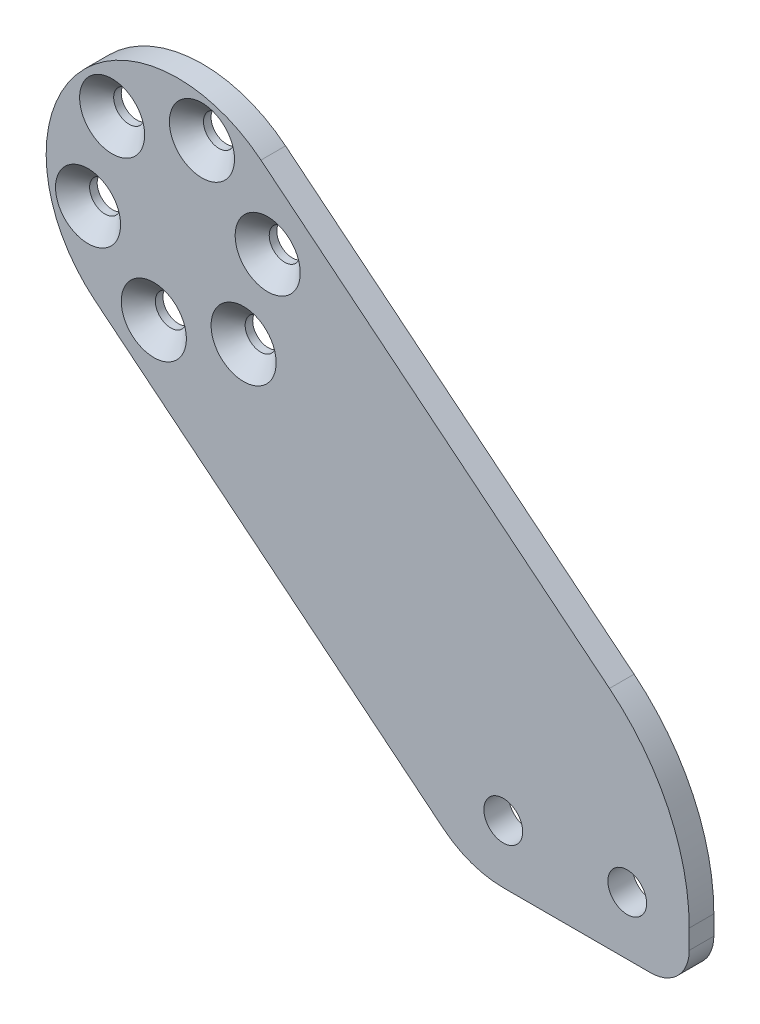
SolidWorks part; units mm, degrees
ref_plane "Front Plane" through (0, 0, 0) normal (0, 0, 1) x (1, 0, 0)
ref_plane "Top Plane" through (0, 0, 0) normal (0, 1, 0) x (1, 0, 0)
ref_plane "Right Plane" through (0, 0, 0) normal (1, 0, 0) x (0, 0, -1)
sketch "Sketch1" plane through (0, 0, 0) normal (0, 0, 1) x (1, 0, 0)
  line L0 (34.2613, -49.7518) -> (-10.7219, -13.1924)
  line L5 (-8.4853, 8.4853) -> (0, 0) construction
  line L6 (0, -12) -> (0, 12) construction
  line L8 (55.7052, -23.367) -> (10.7219, 13.1924)
  line L9 (42, -45) -> (58, -45) construction
  line L10 (42, -45) -> (42, -52.5) construction
  line L14 (66, -45) -> (66, -52.5)
  line L16 (42, -52.5) -> (66, -52.5)
  line L17 (34, -37.5) -> (34, -52.5) construction
  line L18 (34, -52.5) -> (42, -52.5) construction
  line L19 (66, -37.5) -> (66, -45) construction
  line L20 (66, -37.5) -> (34, -37.5) construction
  line L21 (66, -45) -> (58, -45) construction
  line L22 (34.2613, -49.7518) -> (55.7052, -23.367) construction
  line L23 (50, -37.5) -> (50, -52.5) construction
  arc A0 (10.7219, 13.1924) -> (-10.7219, -13.1924) centre (0, 0) ccw
  circle A3 centre (-8.4853, 8.4853) radius 2
  circle A5 centre (3.1058, 11.5911) radius 2
  circle A6 centre (11.5911, 3.1058) radius 2
  circle A7 centre (8.4853, -8.4853) radius 2
  circle A10 centre (0, 0) radius 12 construction
  circle A11 centre (42, -45) radius 2.5
  circle A12 centre (58, -45) radius 2.5
  circle A14 centre (-3.1058, -11.5911) radius 2
  circle A15 centre (-11.5911, -3.1058) radius 2
  circle A16 centre (0, 0) radius 50 construction
  arc A17 (34.2613, -49.7518) -> (42, -52.5) centre (42, -40.2301) ccw
  arc A18 (55.7052, -23.367) -> (66, -45) centre (38.1233, -45) cw
  point P4 (50, -45)
  point P30 (0, 0)
  point P35 (0, 0)
  dimension "D2" = 34
  dimension "D4" = 4
  dimension "D5" = 50
  dimension "D8" = 32
  dimension "D7" = 5
  dimension "D3" = 24
  dimension "D12" = 100
  dimension "D1" = 45
  dimension "D10" = 16
  dimension "D13" = 45
  dimension "D15" = 15
  dimension "D6" = 6
extrude "Boss-Extrude1" add sketch "Sketch1" along normal blind 3.175
fillet "Fillet1" radius 5 1 edges at (66, -52.5, 1.5875)
chamfer "Chamfer1" distance 2.2 angle 45 6 edges at (10.4853, -8.4853, 3.175) (-1.1058, -11.5911, 3.175) (-9.5911, -3.1058, 3.175) (-6.4853, 8.4853, 3.175) (13.5911, 3.1058, 3.175) (5.1058, 11.5911, 3.175)
